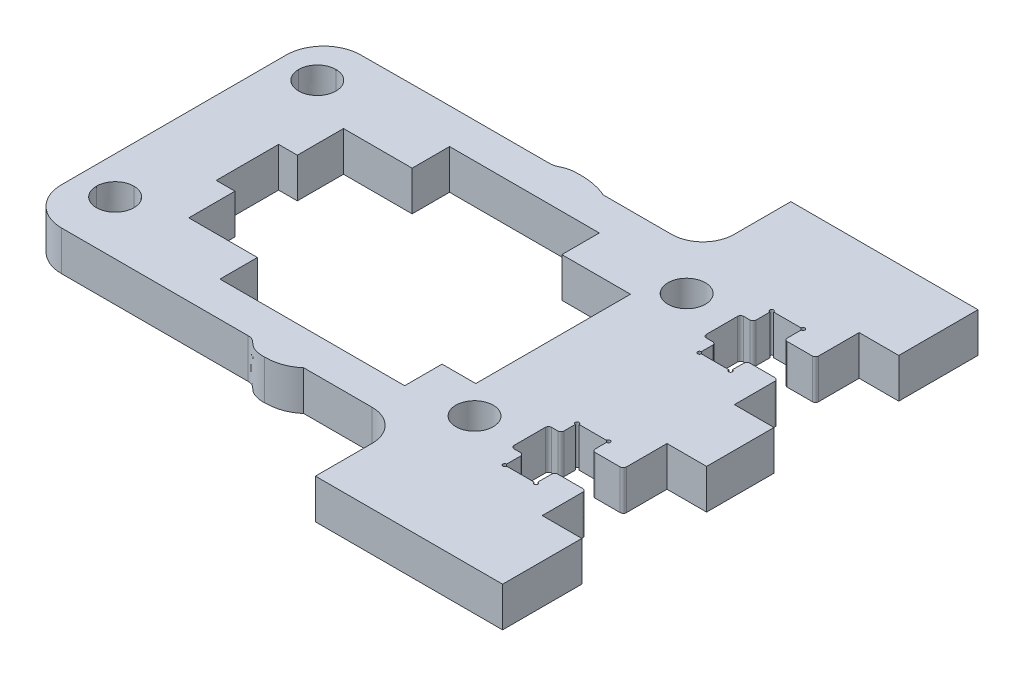
SolidWorks part; units mm, degrees
ref_plane "Front Plane" through (0, 0, 0) normal (0, 0, 1) x (1, 0, 0)
ref_plane "Top Plane" through (0, 0, 0) normal (0, 1, 0) x (1, 0, 0)
ref_plane "Right Plane" through (0, 0, 0) normal (1, 0, 0) x (0, 0, -1)
sketch "Sketch1" plane through (0, 0, 0) normal (0, 1, 0) x (1, 0, 0)
  line L0 (117.4101, 18.6303) -> (141.91, 18.6303) construction
  line L1 (141.91, 37.6804) -> (156.91, 37.6804)
  line L2 (141.91, 37.6804) -> (141.91, 33.1303)
  line L3 (141.91, -0.4196) -> (156.91, -0.4196)
  line L4 (156.91, 37.6804) -> (156.91, 31.3304)
  line L5 (151.435, 18.6304) -> (146.6846, 18.6304) construction
  line L6 (156.91, 31.3304) -> (153.735, 31.3304)
  line L7 (153.735, 21.3304) -> (153.735, 24.5803)
  line L8 (153.735, 21.3304) -> (156.91, 21.3304)
  line L9 (156.91, 21.3304) -> (156.91, 15.9304)
  line L10 (156.91, 15.9304) -> (153.735, 15.9304)
  line L11 (153.735, 15.9304) -> (153.735, 12.6804)
  line L12 (153.735, 5.9304) -> (156.91, 5.9304)
  line L13 (153.735, 26.3304) -> (150.4701, 26.3304) construction
  line L14 (156.91, 5.9304) -> (156.91, -0.4196)
  line L15 (141.91, 24.8303) -> (141.91, 12.4303)
  line L16 (141.91, 4.1305) -> (141.91, -0.4196)
  line L17 (149.985, 28.6032) -> (149.985, 23.1283) construction
  line L18 (153.485, 12.4304) -> (151.485, 12.4304)
  line L19 (151.235, 12.6804) -> (151.235, 13.5054)
  line L20 (150.9752, 13.7304) -> (148.885, 13.7304)
  line L21 (148.735, 13.5054) -> (148.735, 12.6804)
  line L22 (148.485, 12.4304) -> (147.985, 12.4304)
  line L23 (147.735, 12.1804) -> (147.735, 9.6804)
  line L24 (147.985, 9.4304) -> (148.485, 9.4304)
  line L25 (148.735, 9.1804) -> (148.735, 8.1346)
  line L26 (148.885, 7.9304) -> (150.9752, 7.9304)
  line L27 (151.235, 8.1346) -> (151.235, 9.1804)
  line L28 (151.485, 9.4304) -> (153.485, 9.4304)
  line L29 (153.735, 9.1804) -> (153.735, 5.9304)
  line L30 (148.735, 8.6575) -> (151.235, 8.6575) construction
  line L31 (149.985, 8.6575) -> (149.985, 14.1323) construction
  line L32 (148.735, 28.6032) -> (151.235, 28.6032) construction
  line L33 (151.235, 8.1346) -> (151.235, 8.0804)
  line L34 (151.235, 13.5054) -> (151.235, 13.5804)
  line L35 (151.085, 13.7304) -> (150.9752, 13.7304)
  line L36 (148.735, 13.5054) -> (148.735, 13.5804)
  line L37 (148.735, 8.1346) -> (148.735, 8.0804)
  line L38 (151.085, 7.9304) -> (150.9752, 7.9304)
  line L39 (151.085, 29.3303) -> (150.9752, 29.3303)
  line L40 (148.735, 29.1261) -> (148.735, 29.1803)
  line L41 (148.735, 23.7553) -> (148.735, 23.6803)
  line L42 (151.085, 23.5303) -> (150.9752, 23.5303)
  line L43 (151.235, 23.7553) -> (151.235, 23.6803)
  line L44 (151.235, 29.1261) -> (151.235, 29.1803)
  line L45 (151.485, 27.8303) -> (153.485, 27.8303)
  line L46 (151.235, 29.1261) -> (151.235, 28.0803)
  line L47 (148.885, 29.3303) -> (150.9752, 29.3303)
  line L48 (148.735, 28.0803) -> (148.735, 29.1261)
  line L49 (147.985, 27.8303) -> (148.485, 27.8303)
  line L50 (147.735, 25.0803) -> (147.735, 27.5803)
  line L51 (148.485, 24.8303) -> (147.985, 24.8303)
  line L52 (148.735, 23.7553) -> (148.735, 24.5803)
  line L53 (150.9752, 23.5303) -> (148.885, 23.5303)
  line L54 (151.235, 24.5803) -> (151.235, 23.7553)
  line L55 (151.485, 24.8303) -> (153.485, 24.8303)
  line L56 (153.735, 28.0803) -> (153.735, 31.3304)
  line L57 (133.91, 30.6303) -> (139.41, 30.6303)
  line L58 (133.91, 6.6305) -> (139.41, 6.6305)
  line L576 (111.51, 9.6305) -> (111.51, 27.6303)
  line L578 (117.4101, 16.1303) -> (118.91, 16.1303)
  line L579 (118.91, 16.1303) -> (118.91, 12.4303)
  line L580 (118.91, 12.4303) -> (124.41, 12.4303)
  line L581 (124.41, 12.4303) -> (124.41, 9.4305)
  line L582 (124.41, 9.4305) -> (139.21, 9.4305)
  line L583 (139.21, 9.4305) -> (139.21, 12.4303)
  line L584 (139.21, 12.4303) -> (141.91, 12.4303)
  line L586 (141.91, 24.8303) -> (136.41, 24.8303)
  line L587 (136.41, 24.8303) -> (136.41, 27.8303)
  line L588 (136.41, 27.8303) -> (124.41, 27.8303)
  line L589 (124.41, 27.8303) -> (124.41, 24.8303)
  line L590 (124.41, 24.8303) -> (118.91, 24.8303)
  line L591 (118.91, 24.8303) -> (118.91, 21.1303)
  line L592 (118.91, 21.1303) -> (117.4101, 21.1303)
  line L593 (117.4101, 21.1303) -> (117.4101, 16.1303)
  circle A0 centre (144.11, 10.1304) radius 1.4998
  circle A1 centre (144.1101, 27.1303) radius 1.4999
  arc A2 (153.485, 9.4304) -> (153.735, 9.1804) centre (153.485, 9.1804) cw
  arc A3 (153.485, 12.4304) -> (153.735, 12.6804) centre (153.485, 12.6804) ccw
  arc A4 (151.485, 12.4304) -> (151.235, 12.6804) centre (151.485, 12.6804) cw
  arc A5 (151.235, 9.1804) -> (151.485, 9.4304) centre (151.485, 9.1804) cw
  arc A6 (148.485, 9.4304) -> (148.735, 9.1804) centre (148.485, 9.1804) cw
  arc A7 (148.735, 12.6804) -> (148.485, 12.4304) centre (148.485, 12.6804) cw
  arc A8 (147.985, 12.4304) -> (147.735, 12.1804) centre (147.985, 12.1804) ccw
  arc A9 (147.735, 9.6804) -> (147.985, 9.4304) centre (147.985, 9.6804) ccw
  arc A10 (148.735, 8.0804) -> (148.885, 7.9304) centre (148.735, 7.9304) ccw
  arc A11 (151.085, 7.9304) -> (151.235, 8.0804) centre (151.235, 7.9304) ccw
  arc A12 (151.235, 13.5804) -> (151.085, 13.7304) centre (151.235, 13.7304) ccw
  arc A13 (148.885, 13.7304) -> (148.735, 13.5804) centre (148.735, 13.7304) ccw
  arc A14 (153.735, 24.5803) -> (153.485, 24.8303) centre (153.485, 24.5803) ccw
  arc A15 (153.735, 28.0803) -> (153.485, 27.8303) centre (153.485, 28.0803) cw
  arc A16 (148.885, 23.5303) -> (148.735, 23.6803) centre (148.735, 23.5303) cw
  arc A17 (151.235, 23.6803) -> (151.085, 23.5303) centre (151.235, 23.5303) cw
  arc A18 (151.085, 29.3303) -> (151.235, 29.1803) centre (151.235, 29.3303) cw
  arc A19 (148.735, 29.1803) -> (148.885, 29.3303) centre (148.735, 29.3303) cw
  arc A20 (147.735, 27.5803) -> (147.985, 27.8303) centre (147.985, 27.5803) cw
  arc A21 (147.985, 24.8303) -> (147.735, 25.0803) centre (147.985, 25.0803) cw
  arc A22 (148.735, 24.5803) -> (148.485, 24.8303) centre (148.485, 24.5803) ccw
  arc A23 (148.485, 27.8303) -> (148.735, 28.0803) centre (148.485, 28.0803) ccw
  arc A24 (151.235, 28.0803) -> (151.485, 27.8303) centre (151.485, 28.0803) ccw
  arc A25 (151.485, 24.8303) -> (151.235, 24.5803) centre (151.485, 24.5803) ccw
  arc A26 (139.41, 6.6305) -> (141.91, 4.1305) centre (139.41, 4.1305) cw
  arc A27 (139.41, 30.6303) -> (141.91, 33.1303) centre (139.41, 33.1303) ccw
  spline S312 degree 3 poles (116.01, 27.1303) (116.01, 26.3018) (115.3385, 25.6303) (114.5101, 25.6303) knots 0 0 0 0 0.2 0.2 0.2 0.2
  spline S313 degree 3 poles (114.5101, 25.6303) (113.6816, 25.6302) (113.0101, 26.3018) (113.0101, 27.1302) knots 0.2 0.2 0.2 0.2 0.4 0.4 0.4 0.4
  spline S314 degree 3 poles (113.0101, 27.1302) (113.01, 27.9587) (113.6816, 28.6302) (114.51, 28.6303) knots 0.4 0.4 0.4 0.4 0.6 0.6 0.6 0.6
  spline S315 degree 3 poles (114.51, 28.6303) (115.3385, 28.6303) (116.01, 27.9587) (116.01, 27.1303) knots 0.6 0.6 0.6 0.6 1 1 1 1
  spline S320 degree 3 poles (116.01, 10.9306) (116.01, 10.1022) (115.3384, 9.4305) (114.5101, 9.4305) knots 0 0 0 0 0.2 0.2 0.2 0.2
  spline S321 degree 3 poles (114.5101, 9.4305) (113.6817, 9.4305) (113.01, 10.1022) (113.01, 10.9305) knots 0.2 0.2 0.2 0.2 0.4 0.4 0.4 0.4
  spline S322 degree 3 poles (113.01, 10.9305) (113.01, 11.7589) (113.6817, 12.4304) (114.51, 12.4304) knots 0.4 0.4 0.4 0.4 0.6 0.6 0.6 0.6
  spline S323 degree 3 poles (114.51, 12.4304) (115.3384, 12.4304) (116.01, 11.7589) (116.01, 10.9306) knots 0.6 0.6 0.6 0.6 1 1 1 1
  spline S328 degree 3 poles (111.51, 27.6303) (111.51, 28.4259) (111.8262, 29.189) (112.3888, 29.7516) knots 0.058824 0.058824 0.058824 0.058824 0.117647 0.117647 0.117647 0.117647
  spline S329 degree 3 poles (112.3888, 29.7516) (112.9514, 30.3142) (113.7144, 30.6303) (114.51, 30.6303) knots 0.117647 0.117647 0.117647 0.117647 0.176471 0.176471 0.176471 0.176471
  spline S330 degree 3 poles (114.51, 30.6303) (114.4972, 30.6508) (123.8342, 30.6751) (129.5578, 30.6658) knots 0.176471 0.176471 0.176471 0.176471 0.235294 0.235294 0.235294 0.235294
  spline S331 degree 3 poles (129.5578, 30.6658) (130.305, 30.6646) (130.244, 31.1022) (131.5888, 31.1022) knots 0.235294 0.235294 0.235294 0.235294 0.294118 0.294118 0.294118 0.294118
  spline S332 degree 3 poles (131.5888, 31.1022) (133.0006, 31.1022) (133.901, 30.6448) (133.91, 30.6303) knots 0.294118 0.294118 0.294118 0.294118 0.352941 0.352941 0.352941 0.352941
  spline S337 degree 2 poles (133.91, 6.6305) (132.9823, 5.8019) (131.5888, 5.8019) knots 0.647059 0.647059 0.647059 0.705882 0.705882 0.705882
  spline S338 degree 3 poles (131.5888, 5.8019) (130.0782, 5.8019) (130.2699, 6.6305) (129.4696, 6.6305) knots 0.705882 0.705882 0.705882 0.705882 0.764706 0.764706 0.764706 0.764706
  spline S339 degree 2 poles (129.4696, 6.6305) (123.7428, 6.6305) (114.51, 6.6305) knots 0.764706 0.764706 0.764706 0.823529 0.823529 0.823529
  spline S340 degree 3 poles (114.51, 6.6305) (113.7144, 6.6305) (112.9514, 6.9465) (112.3888, 7.5091) knots 0.823529 0.823529 0.823529 0.823529 0.882353 0.882353 0.882353 0.882353
  spline S341 degree 3 poles (112.3888, 7.5091) (111.8262, 8.0717) (111.51, 8.8348) (111.51, 9.6305) knots 0.882353 0.882353 0.882353 0.882353 1 1 1 1
  point P34 (153.735, 9.4304)
  point P51 (147.735, 12.4304)
  point P54 (147.735, 9.4304)
  point P119 (147.735, 27.8303)
  point P120 (147.735, 24.8303)
  dimension "D10" = 0.25
  dimension "D11" = 0.3
  dimension "D18" = 0.3
  dimension "D19" = 0.25
  dimension "D20" = 2.5
  dimension "D12" = 0.3
  dimension "D14" = 0.3
  dimension "D1" = 15
  dimension "D2" = 38.1
  dimension "D3" = 10
  dimension "D4" = 3.175
  dimension "D5" = 6.35
  dimension "D6" = 3.175
  dimension "D7" = 6.35
  dimension "D8" = 10
  dimension "D9" = 3
  dimension "D13" = 2.5
  dimension "D15" = 6
  dimension "D16" = 2.5
  dimension "D17" = 5.8
  dimension "D25" = 2.5
  dimension "D26" = 2.5
extrude "Boss-Extrude1" add sketch "Sketch1" along normal blind 3.175
